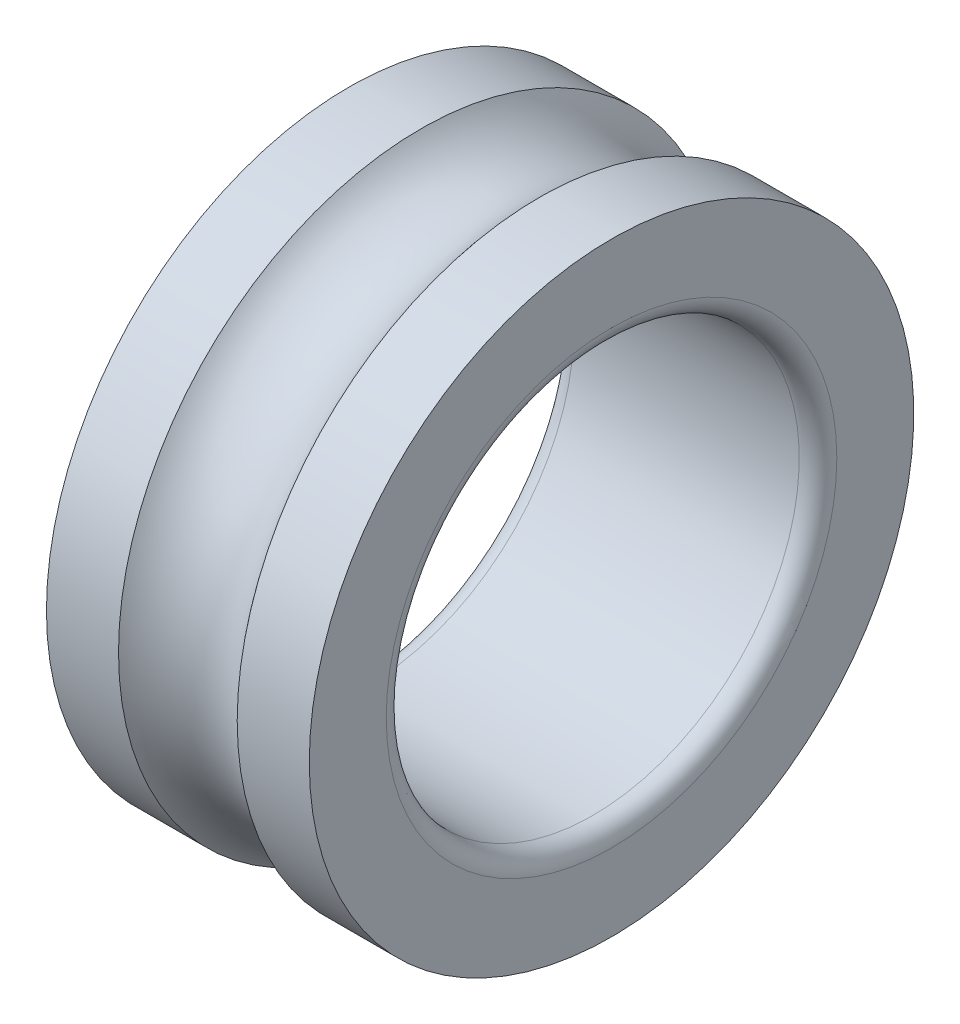
SolidWorks part; units mm, degrees
ref_plane "Front Plane" through (0, 0, 0) normal (0, 0, 1) x (1, 0, 0)
ref_plane "Top Plane" through (0, 0, 0) normal (0, 1, 0) x (1, 0, 0)
ref_plane "Right Plane" through (0, 0, 0) normal (1, 0, 0) x (0, 0, -1)
ref_plane "Plane1"
sketch "Sketch1" plane through (0, 0, 0) normal (0, 0, 1) x (1, 0, 0)
  line L0 (1, 11) -> (13, 11)
  line L1 (14, 12) -> (14, 16.1)
  line L2 (14, 16.1) -> (10.1612, 16.1)
  line L3 (3.8388, 16.1) -> (0, 16.1)
  line L4 (0, 16.1) -> (0, 12)
  line L5 (50, 0) -> (-50, 0) construction
  arc A0 (0, 12) -> (1, 11) centre (1, 12) ccw
  arc A1 (13, 11) -> (14, 12) centre (13, 12) ccw
  arc A2 (3.8388, 16.1) -> (10.1612, 16.1) centre (7, 18.5) ccw
revolve "Revolução1" add sketch "Sketch1" angle 360 about L5
